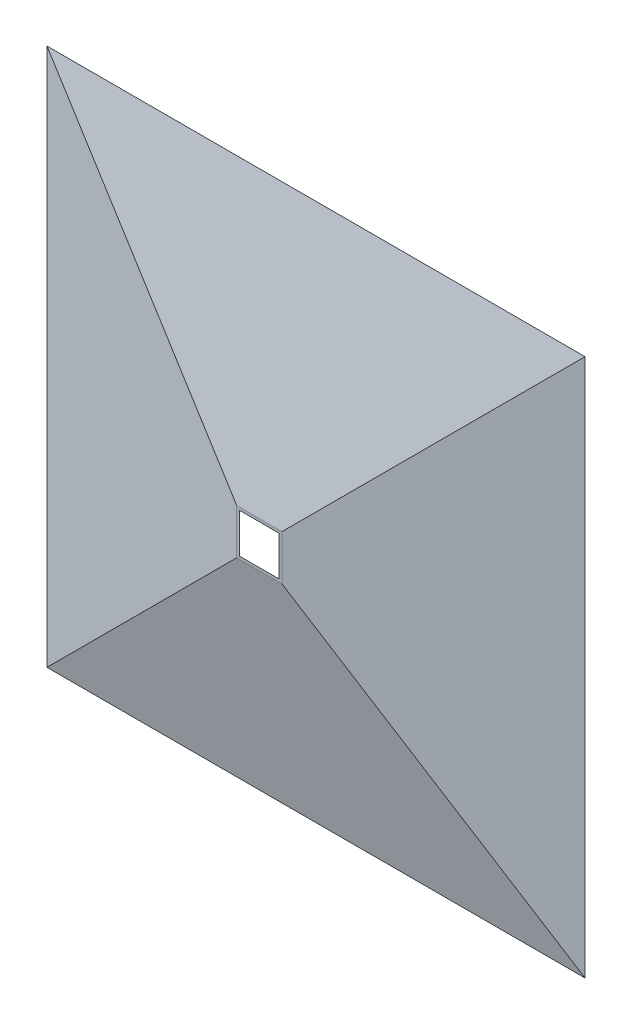
SolidWorks part; units mm, degrees
ref_plane "前视基准面" through (0, 0, 0) normal (0, 0, 1) x (1, 0, 0)
ref_plane "上视基准面" through (0, 0, 0) normal (0, 1, 0) x (1, 0, 0)
ref_plane "右视基准面" through (0, 0, 0) normal (1, 0, 0) x (0, 0, -1)
sketch "草图1" plane through (0, 0, 0) normal (0, 0, 1) x (1, 0, 0)
  line L1 (-475, 475) -> (475, 475)
  line L2 (-475, 475) -> (-475, -475)
  line L3 (-475, -475) -> (475, -475)
  line L4 (475, 475) -> (475, -475)
  line L5 (-475, 475) -> (475, -475) construction
  line L6 (-475, -475) -> (475, 475) construction
  point P0 (0, 0)
  dimension "D1" = 950
  dimension "D2" = 950
ref_plane "基准面1" through (0, 0, 100) normal (0, 0, 1) x (1, 0, 0)
sketch "草图2" plane through (0, 0, 100) normal (0, 0, 1) x (1, 0, 0)
  line L0 (-475, 475) -> (475, -475) construction
  line L1 (-40, 40) -> (40, 40)
  line L2 (-40, 40) -> (-40, -40)
  line L3 (-40, -40) -> (40, -40)
  line L4 (40, 40) -> (40, -40)
  line L5 (-40, 40) -> (40, -40) construction
  line L6 (-40, -40) -> (40, 40) construction
  point P0 (0, 0)
  dimension "D1" = 80
loft "放样1" add profiles "草图1", "草图2"
sketch "草图3" plane through (0, 0, 0) normal (0, 0, -1) x (-1, 0, 0)
  line L1 (470, -470) -> (-470, -470)
  line L2 (470, -470) -> (470, 470)
  line L3 (470, 470) -> (-470, 470)
  line L4 (-470, -470) -> (-470, 470)
  line L5 (470, -470) -> (-470, 470) construction
  line L6 (470, 470) -> (-470, -470) construction
  point P0 (0, 0)
  dimension "D1" = 940
  dimension "D2" = 940
sketch "草图4" plane through (0, 0, 100) normal (0, 0, 1) x (1, 0, 0)
  line L0 (-470, 470) -> (470, -470) construction
  line L1 (-35, 35) -> (35, 35)
  line L2 (-35, 35) -> (-35, -35)
  line L3 (-35, -35) -> (35, -35)
  line L4 (35, 35) -> (35, -35)
  line L5 (-35, 35) -> (35, -35) construction
  line L6 (-35, -35) -> (35, 35) construction
  point P0 (0, 0)
  dimension "D1" = 70
loft "切除-放样1" cut profiles "草图3", "草图4"
